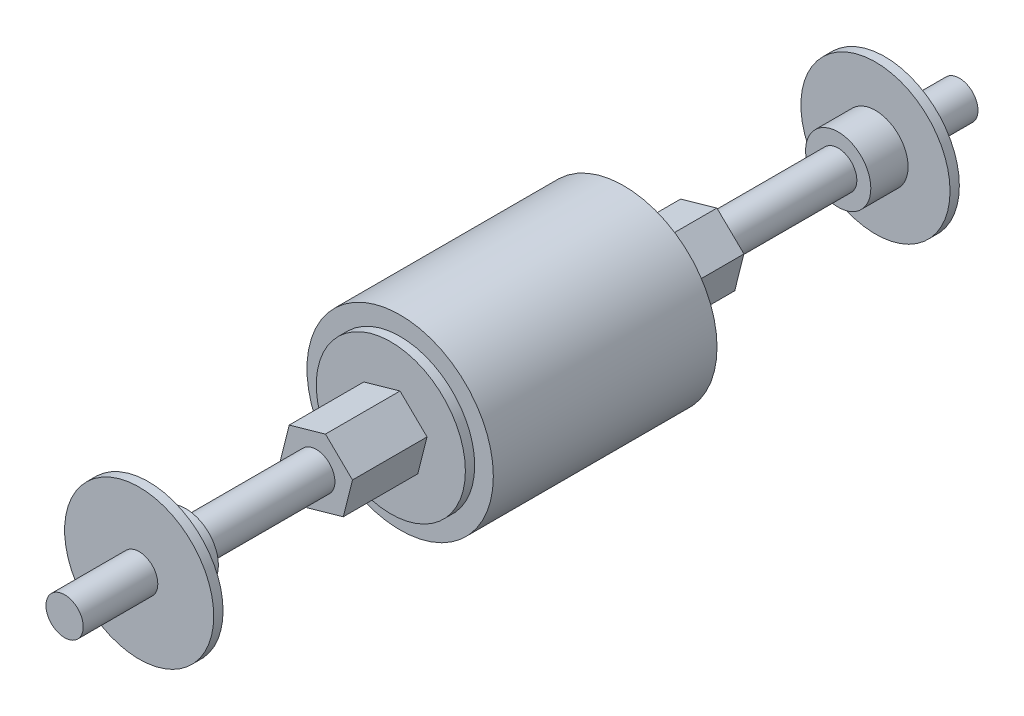
SolidWorks part; units mm, degrees
ref_plane "Front Plane" through (0, 0, 0) normal (0, 0, 1) x (1, 0, 0)
ref_plane "Top Plane" through (0, 0, 0) normal (0, 1, 0) x (1, 0, 0)
ref_plane "Right Plane" through (0, 0, 0) normal (1, 0, 0) x (0, 0, -1)
sketch "Sketch1" plane through (0, 0, 0) normal (0, 0, 1) x (1, 0, 0)
  circle A0 centre (0, 0) radius 15.875
  point P3 (0, 0)
  dimension "D1" = 31.75
extrude "Boss-Extrude1" add sketch "Sketch1" along normal blind 19.05
sketch "Sketch2" plane through (0, 0, 19.05) normal (0, 0, 1) x (1, 0, 0)
  circle A0 centre (0, 0) radius 12.7
  dimension "D1" = 25.4
extrude "Boss-Extrude2" add sketch "Sketch2" along normal blind 1.5875 contours A0
sketch "Sketch3" plane through (0, 0, 20.6375) normal (0, 0, 1) x (1, 0, 0)
  line L1 (4.6031, -4.4692) -> (6.172, 1.7518)
  line L2 (6.172, 1.7518) -> (1.5689, 6.221)
  line L3 (1.5689, 6.221) -> (-4.6031, 4.4692)
  line L4 (-4.6031, 4.4692) -> (-6.172, -1.7518)
  line L5 (-6.172, -1.7518) -> (-1.5689, -6.221)
  line L6 (-1.5689, -6.221) -> (4.6031, -4.4692)
  circle A0 centre (0, 0) radius 5.5562 construction
  dimension "D1" = 5.5562
extrude "Boss-Extrude3" add sketch "Sketch3" along normal blind 12.7
sketch "Sketch4" plane through (0, 0, 33.3375) normal (0, 0, 1) x (1, 0, 0)
  circle A0 centre (0, 0) radius 3.175
  dimension "D1" = 6.35
extrude "Boss-Extrude4" add sketch "Sketch4" along normal blind 22.225
sketch "Sketch5" plane through (0, 0, 55.5625) normal (0, 0, 1) x (1, 0, 0)
  circle A0 centre (0, 0) radius 5.5562
  dimension "D1" = 11.1125
extrude "Boss-Extrude6" add sketch "Sketch5" along normal blind 6.35
sketch "Sketch6" plane through (0, 0, 61.9125) normal (0, 0, 1) x (1, 0, 0)
  circle A0 centre (0, 0) radius 12.7
  dimension "D1" = 25.4
extrude "Boss-Extrude7" add sketch "Sketch6" along normal blind 1.5875
sketch "Sketch7" plane through (0, 0, 63.5) normal (0, 0, 1) x (1, 0, 0)
  circle A0 centre (0, 0) radius 3.175
  dimension "D1" = 6.35
extrude "Boss-Extrude8" add sketch "Sketch7" along normal blind 12.7
mirror "Mirror1" about plane through (0, 0, 0) normal (0, 0, 1) of "Boss-Extrude8", "Boss-Extrude7", "Boss-Extrude4", "Boss-Extrude6", "Boss-Extrude3", "Boss-Extrude2", "Boss-Extrude1"
